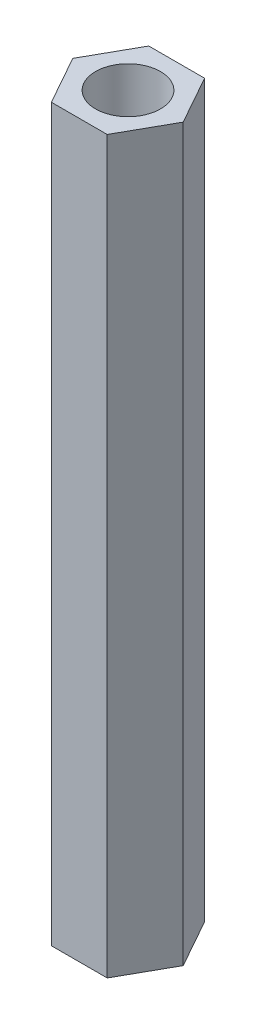
SolidWorks part; units mm, degrees
ref_plane "前视基准面" through (0, 0, 0) normal (0, 0, 1) x (1, 0, 0)
ref_plane "上视基准面" through (0, 0, 0) normal (0, 1, 0) x (1, 0, 0)
ref_plane "右视基准面" through (0, 0, 0) normal (1, 0, 0) x (0, 0, -1)
other "Configuration Table"
sketch "草图1" plane through (0, 0, 0) normal (0, 1, 0) x (1, 0, 0)
  line L1 (1.7193, -3) -> (3.4, 0)
  line L2 (3.4, 0) -> (1.7193, 3)
  line L3 (1.7193, 3) -> (-1.7193, 3)
  line L4 (-1.7193, 3) -> (-3.4, 0)
  line L5 (-3.4, 0) -> (-1.7193, -3)
  line L6 (-1.7193, -3) -> (1.7193, -3)
  circle A0 centre (0, 0) radius 2
  point P1 (0, 3)
  point P9 (0, -3)
  dimension "D3" = 4
  dimension "D1" = 6
  dimension "D2" = 6.8
extrude "凸台-拉伸1" add sketch "草图1" along normal blind 45
